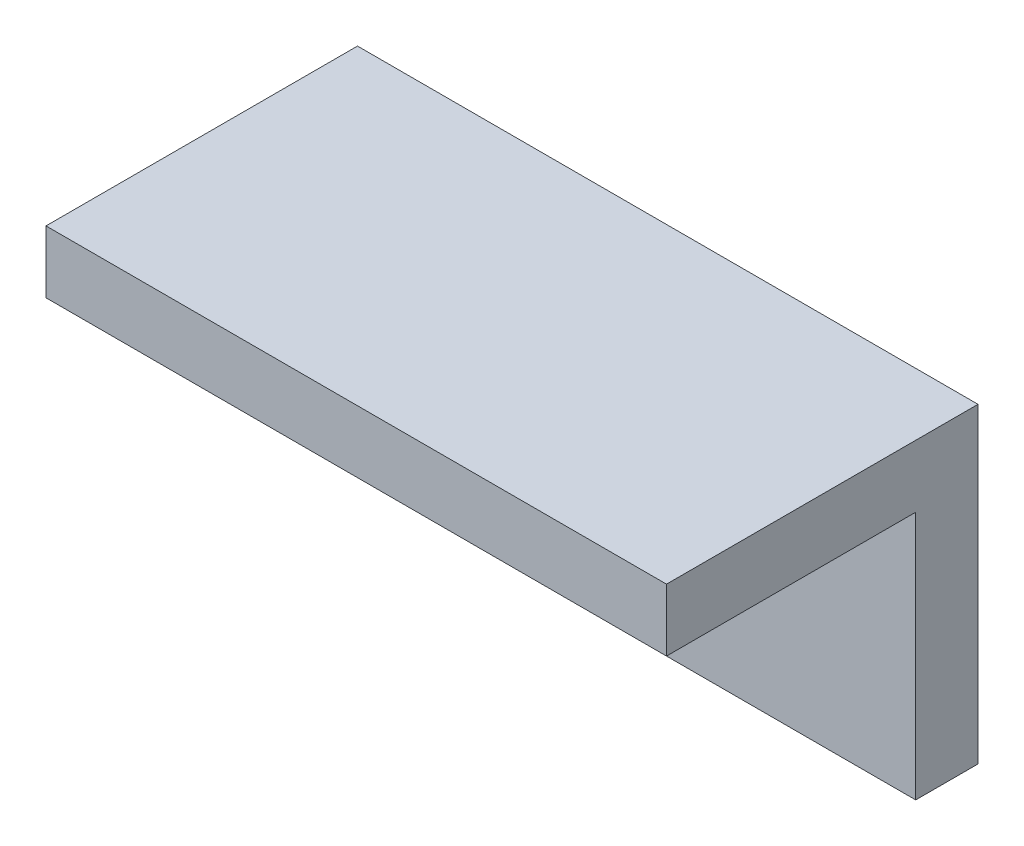
SolidWorks part; units mm, degrees
ref_plane "Front Plane" through (0, 0, 0) normal (0, 0, 1) x (1, 0, 0)
ref_plane "Top Plane" through (0, 0, 0) normal (0, 1, 0) x (1, 0, 0)
ref_plane "Right Plane" through (0, 0, 0) normal (1, 0, 0) x (0, 0, -1)
sketch "Sketch1" plane through (0, 0, 0) normal (1, 0, 0) x (0, 0, -1)
  line L0 (0, 0) -> (0, 15.875)
  line L1 (0, 15.875) -> (-15.875, 15.875)
  line L2 (-15.875, 15.875) -> (-15.875, 12.7)
  line L3 (-15.875, 12.7) -> (-3.175, 12.7)
  line L4 (-3.175, 12.7) -> (-3.175, 0)
  line L5 (-3.175, 0) -> (0, 0)
  dimension "D1" = 3.175
  dimension "D2" = 12.7
  dimension "D3" = 12.7
extrude "Boss-Extrude1" add sketch "Sketch1" along normal blind 31.623
